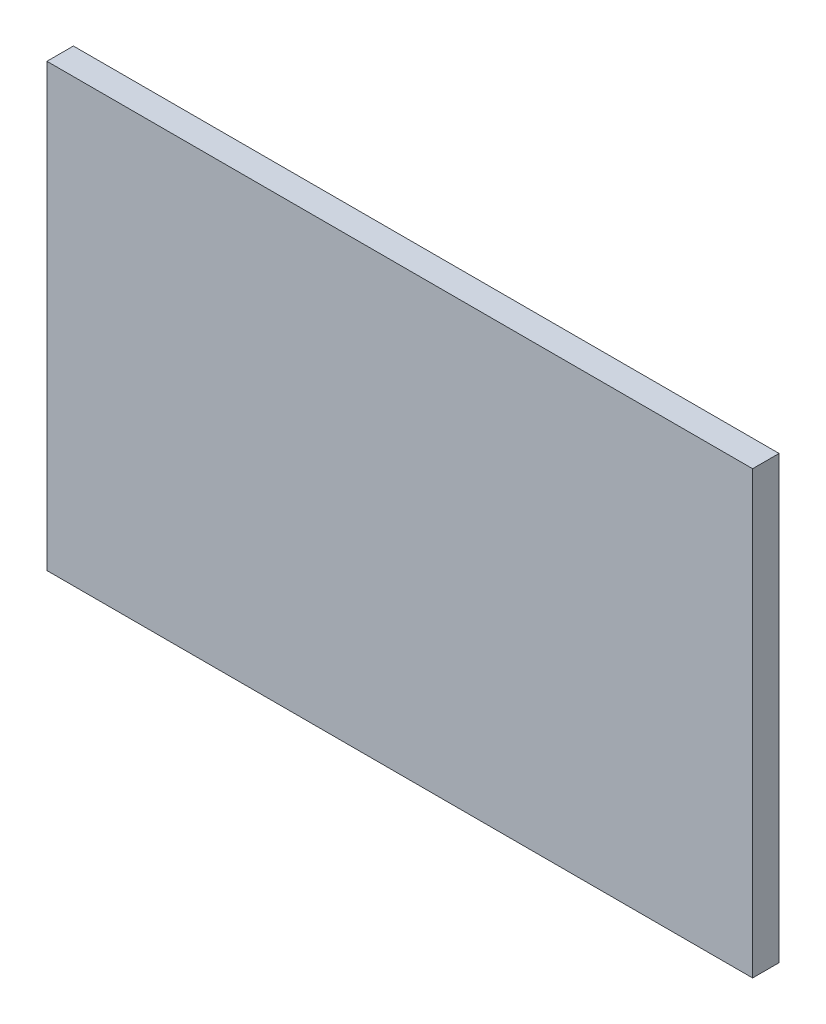
SolidWorks part; units mm, degrees
ref_plane "前视基准面" through (0, 0, 0) normal (0, 0, 1) x (1, 0, 0)
ref_plane "上视基准面" through (0, 0, 0) normal (0, 1, 0) x (1, 0, 0)
ref_plane "右视基准面" through (0, 0, 0) normal (1, 0, 0) x (0, 0, -1)
other "Configuration Table"
sketch "草图1" plane through (0, 0, 0) normal (0, 0, 1) x (1, 0, 0)
  line L1 (-32.2239, 28.4851) -> (47.7761, 28.4851)
  line L2 (-32.2239, 28.4851) -> (-32.2239, -21.5149)
  line L3 (-32.2239, -21.5149) -> (47.7761, -21.5149)
  line L4 (47.7761, 28.4851) -> (47.7761, -21.5149)
  dimension "D1" = 50
  dimension "D2" = 80
extrude "凸台-拉伸1" add sketch "草图1" along normal blind 3
